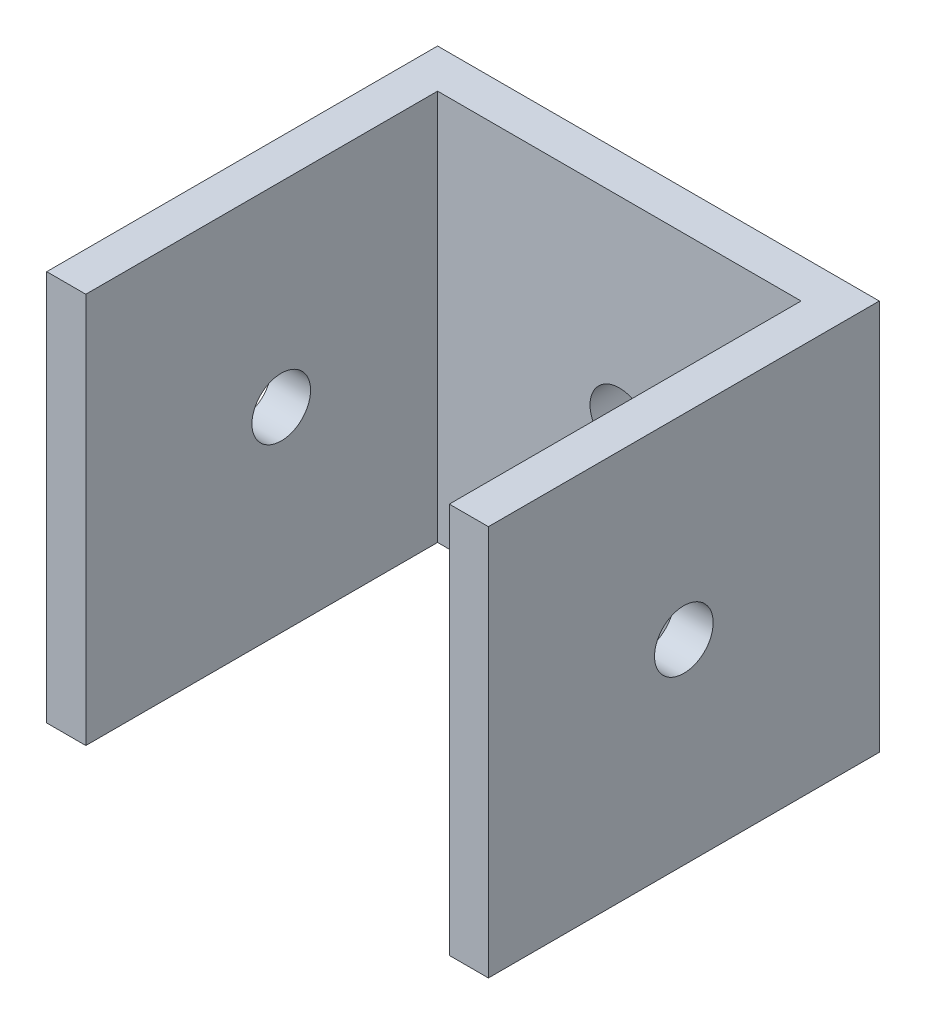
SolidWorks part; units mm, degrees
ref_plane "Front Plane" through (0, 0, 0) normal (0, 0, 1) x (1, 0, 0)
ref_plane "Top Plane" through (0, 0, 0) normal (0, 1, 0) x (1, 0, 0)
ref_plane "Right Plane" through (0, 0, 0) normal (1, 0, 0) x (0, 0, -1)
sketch "Sketch1" plane through (0, 0, 0) normal (0, 1, 0) x (1, 0, 0)
  line L0 (-56.5, 0) -> (56.5, 0)
  line L1 (56.5, 0) -> (56.5, -100)
  line L2 (56.5, -100) -> (46.5, -100)
  line L3 (46.5, -100) -> (46.5, -10)
  line L4 (46.5, -10) -> (-46.5, -10)
  line L5 (0, 0) -> (0, -33.2117) construction
  line L6 (-56.5, -100) -> (-46.5, -100)
  line L7 (-56.5, 0) -> (-56.5, -100)
  line L8 (-46.5, -100) -> (-46.5, -10)
  point P11 (0, -10)
  dimension "D1" = 113
  dimension "D2" = 100
  dimension "D3" = 10
  dimension "D4" = 90
extrude "Boss-Extrude1" add sketch "Sketch1" along normal blind 100
sketch "Sketch2" plane through (56.5, 0, 0) normal (1, 0, 0) x (0, 0, -1)
  line L0 (-100, 50) -> (0, 50) construction
  line L3 (-100, 100) -> (-100, 0) construction
  line L4 (0, 100) -> (0, 0) construction
  circle A0 centre (-50, 50) radius 7.5
  point P3 (-50, 50)
  dimension "D1" = 15
extrude "Cut-Extrude1" cut sketch "Sketch2" against normal blind 140
sketch "Sketch3" plane through (0, 0, 0) normal (0, 0, -1) x (-1, 0, 0)
  line L0 (-56.5, 50) -> (56.5, 50) construction
  line L1 (-56.5, 100) -> (-56.5, 0) construction
  line L2 (56.5, 100) -> (56.5, 0) construction
  circle A0 centre (0, 50) radius 7.5
  dimension "D1" = 15
extrude "Cut-Extrude2" cut sketch "Sketch3" against normal blind 140
